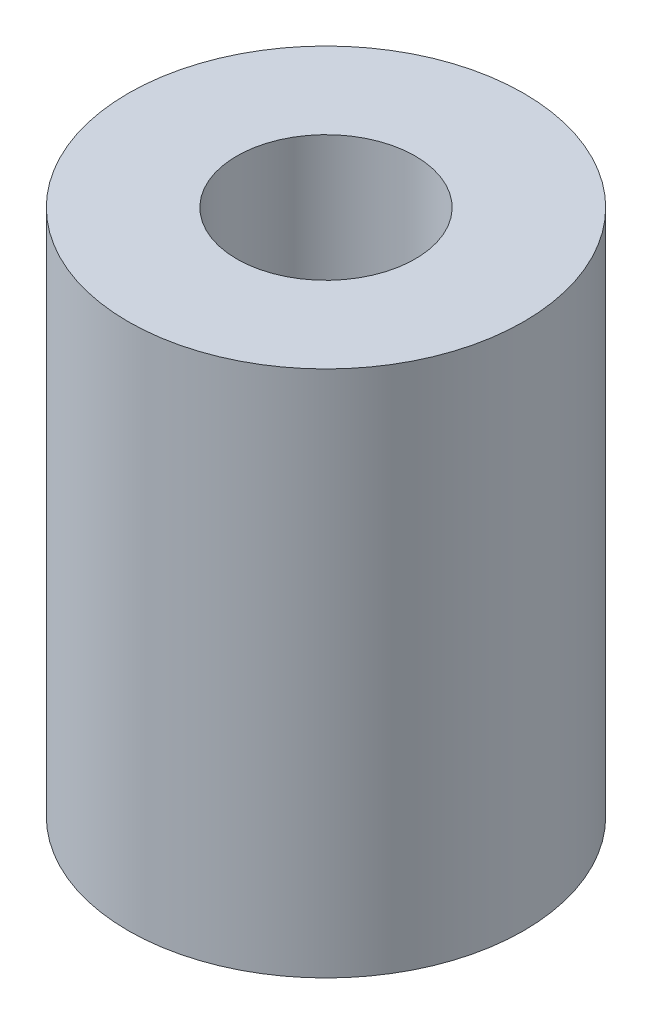
SolidWorks part; units mm, degrees
ref_plane "Front Plane" through (0, 0, 0) normal (0, 0, 1) x (1, 0, 0)
ref_plane "Top Plane" through (0, 0, 0) normal (0, 1, 0) x (1, 0, 0)
ref_plane "Right Plane" through (0, 0, 0) normal (1, 0, 0) x (0, 0, -1)
sketch "Sketch1" plane through (0, 0, 0) normal (0, 1, 0) x (1, 0, 0)
  circle A0 centre (0, 0) radius 11.0833
  circle A1 centre (0, 0) radius 5
  dimension "D1" = 22.1667
  dimension "D2" = 10
extrude "Boss-Extrude3" add sketch "Sketch1" along normal mid plane 29.5556
equation "\"D1@Sketch1\"=(\"Upper_Mount_largest_radius\"/0.8)/1.5"
equation "\"D1\"= \"SHOCK_MOUNT_BUSHING_DIA\" / 0.4375"
equation "\"D1@Boss-Extrude3\"=((\"Upper_Mount_largest_radius\"/1.2)/1.5)*2"
equation "\"Upper_Mount_largest_radius\" =26.6"
equation "\"Upper_mount_wall_thickness\" =4"
equation "\"Lower_Mount_piston_rod_length\" =149"
equation "\"Lower_Mount_piston_rod_radius\"\t=3.4925"
equation "\"Piston_orifice_dia\"=0.30711"
equation "\"Spring_inner_dia\" =80"
equation "\"Spring_wire_dia\" =8"
